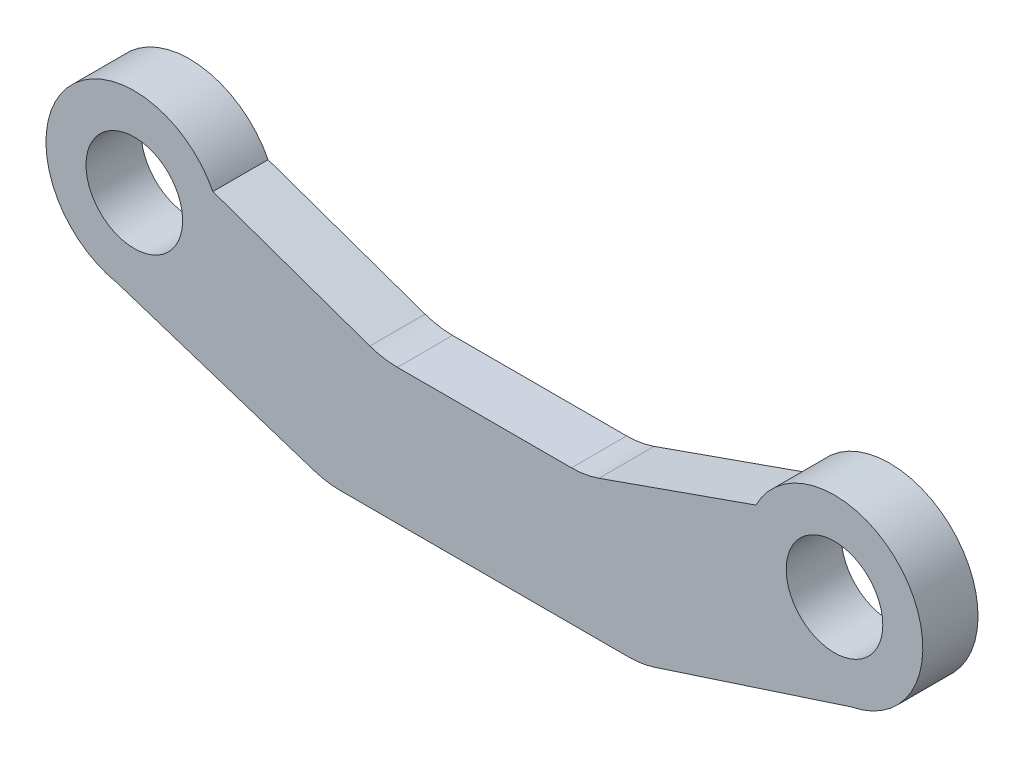
SolidWorks part; units mm, degrees
ref_plane "Alzado" through (0, 0, 0) normal (0, 0, 1) x (1, 0, 0)
ref_plane "Planta" through (0, 0, 0) normal (0, 1, 0) x (1, 0, 0)
ref_plane "Vista lateral" through (0, 0, 0) normal (1, 0, 0) x (0, 0, -1)
sketch "Croquis1" plane through (0, 0, 0) normal (0, 0, 1) x (1, 0, 0)
  line L0 (200, 800) -> (1000, 800) construction
  line L1 (13.8712, 23.2747) -> (24.3301, 23.2747)
  line L2 (25.2578, 23.4218) -> (32.4056, 25.7461)
  line L3 (15.9484, 28.1747) -> (22.2529, 28.1747)
  line L4 (12.9434, 23.4218) -> (5.7956, 25.7461)
  line L5 (14.952, 28.345) -> (9.2656, 30.3471)
  line L6 (23.2493, 28.345) -> (28.9356, 30.3471)
  circle A2 centre (31.7819, 28.8847) radius 1.75
  arc A3 (32.4056, 25.7461) -> (28.9356, 30.3471) centre (31.7819, 28.8847) ccw
  circle A4 centre (6.4194, 28.8847) radius 1.75
  arc A5 (5.7956, 25.7461) -> (9.2656, 30.3471) centre (6.4194, 28.8847) cw
  arc A6 (24.3301, 23.2747) -> (25.2578, 23.4218) centre (24.3301, 26.2747) ccw
  arc A7 (12.9434, 23.4218) -> (13.8712, 23.2747) centre (13.8712, 26.2747) ccw
  arc A8 (22.2529, 28.1747) -> (23.2493, 28.345) centre (22.2529, 31.1747) ccw
  arc A9 (14.952, 28.345) -> (15.9484, 28.1747) centre (15.9484, 31.1747) ccw
  point P16 (19.1006, 23.2747)
  point P17 (19.1006, 28.1747)
  point P18 (19.1006, 23.2747)
  point P19 (19.1006, 28.1747)
  point P20 (19.1006, 28.1747)
  point P23 (24.8056, 23.2747)
  point P26 (13.3956, 23.2747)
  point P29 (22.7656, 28.1747)
  point P32 (15.4356, 28.1747)
  dimension "D2" = 3.5
  dimension "D3" = 6.4
  dimension "D1" = 3
  dimension "D4" = 7.6
  dimension "D5" = 6.17
extrude "Saliente-Extruir1" add sketch "Croquis1" along normal blind 2
